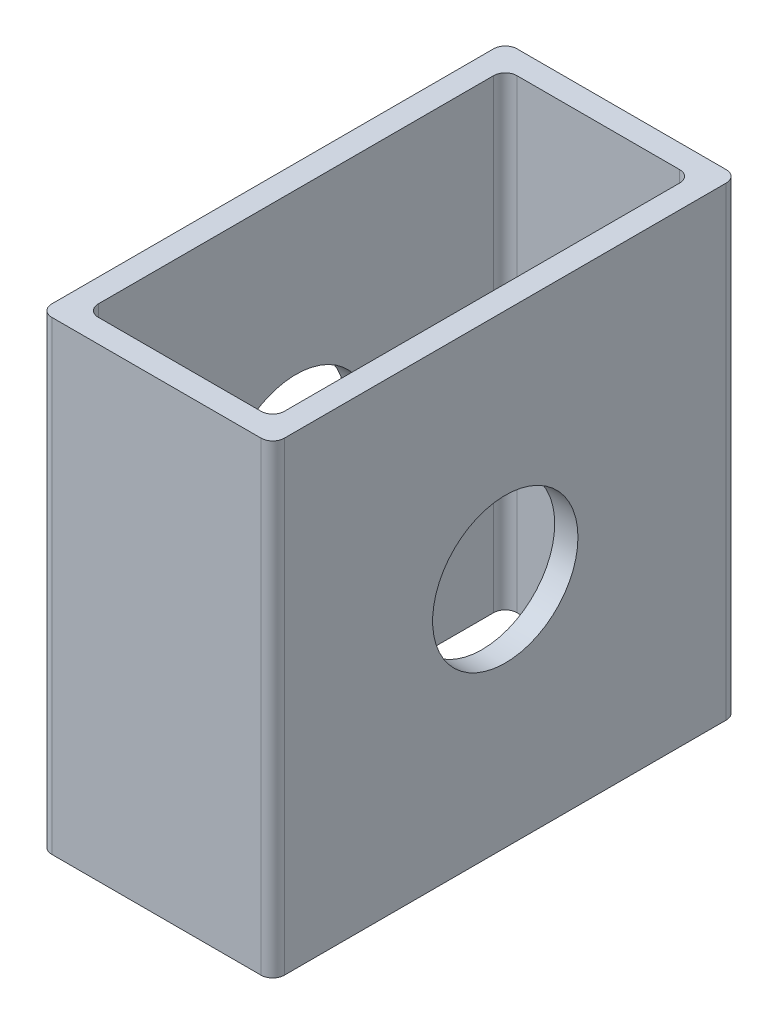
SolidWorks part; units mm, degrees
ref_plane "Plan de face" through (0, 0, 0) normal (0, 0, 1) x (1, 0, 0)
ref_plane "Plan de dessus" through (0, 0, 0) normal (0, 1, 0) x (1, 0, 0)
ref_plane "Plan de droite" through (0, 0, 0) normal (1, 0, 0) x (0, 0, -1)
sketch "Esquisse2" plane through (0, 0, 0) normal (0, 1, 0) x (1, 0, 0)
  line L0 (6, 4) -> (34, 4)
  line L1 (2, 0) -> (38, 0)
  line L2 (0, 2) -> (0, 78)
  line L3 (2, 80) -> (38, 80)
  line L4 (40, 2) -> (40, 78)
  line L5 (36, 6) -> (36, 74)
  line L6 (6, 76) -> (34, 76)
  line L7 (4, 6) -> (4, 74)
  line L8 (4, 4) -> (36, 4) construction
  line L9 (36, 4) -> (36, 76) construction
  line L10 (4, 76) -> (36, 76) construction
  line L11 (4, 4) -> (4, 76) construction
  line L12 (0, 0) -> (40, 0) construction
  line L13 (0, 0) -> (0, 80) construction
  line L14 (0, 80) -> (40, 80) construction
  line L15 (40, 0) -> (40, 80) construction
  arc A0 (34, 4) -> (36, 6) centre (34, 6) ccw
  arc A1 (36, 74) -> (34, 76) centre (34, 74) ccw
  arc A2 (6, 76) -> (4, 74) centre (6, 74) ccw
  arc A3 (4, 6) -> (6, 4) centre (6, 6) ccw
  arc A4 (2, 0) -> (0, 2) centre (2, 2) cw
  arc A5 (0, 78) -> (2, 80) centre (2, 78) cw
  arc A6 (38, 80) -> (40, 78) centre (38, 78) cw
  arc A7 (40, 2) -> (38, 0) centre (38, 2) cw
  point P24 (0, 0)
  dimension "D4" = 2
  dimension "D1" = 80
  dimension "D2" = 40
  dimension "D3" = 4
extrude "Boss.-Extru.1" add sketch "Esquisse2" along normal blind 705
sketch "Esquisse3" plane through (40, 0, 0) normal (1, 0, 0) x (0, 0, -1)
  line L0 (80, 90) -> (40, 90) construction
  line L1 (40, 90) -> (40, 0) construction
  line L2 (40, 90) -> (40, 665) construction
  line L4 (2, 0) -> (78, 0) construction
  line L5 (80, 705) -> (80, 0) construction
  circle A0 centre (40, 90) radius 10.125
  circle A1 centre (40, 665) radius 12.5
  dimension "D1" = 20.25
  dimension "D2" = 90
  dimension "D3" = 25
  dimension "D4" = 575
extrude "Enlèv. mat.-Extru.1" cut sketch "Esquisse3" against normal through all
sketch "Esquisse4" plane through (0, 0, 0) normal (0, 0, 1) x (1, 0, 0)
  line L0 (40, 705) -> (40, 625)
  line L1 (0, 705) -> (0, 0) construction
  line L2 (0, 705) -> (0, 625)
  line L3 (40, 705) -> (0, 705)
  line L5 (0, 625) -> (40, 625)
  line L6 (40, 705) -> (40, 0) construction
  line L7 (2, 705) -> (38, 705) construction
  line L8 (-293.7947, 865.3775) -> (324.4758, 865.3775)
  line L9 (-293.7947, 865.3775) -> (-293.7947, -34.4631)
  line L10 (-293.7947, -34.4631) -> (324.4758, -34.4631)
  line L11 (324.4758, 865.3775) -> (324.4758, -34.4631)
  dimension "D2" = 80
extrude "Enlèv. mat.-Extru.2" cut sketch "Esquisse4" against normal through all
